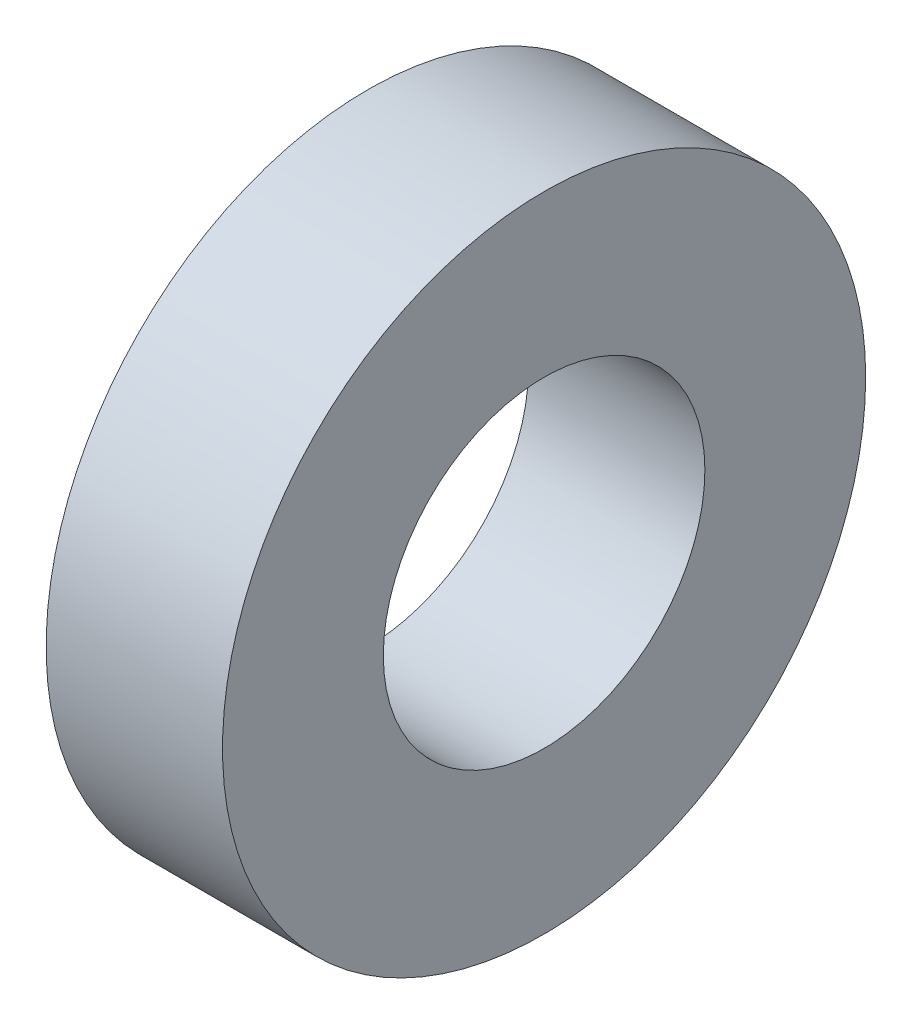
SolidWorks part; units mm, degrees
ref_plane "Front Plane" through (0, 0, 0) normal (0, 0, 1) x (1, 0, 0)
ref_plane "Top Plane" through (0, 0, 0) normal (0, 1, 0) x (1, 0, 0)
ref_plane "Right Plane" through (0, 0, 0) normal (1, 0, 0) x (0, 0, -1)
sketch "Sketch1" plane through (0, 0, 0) normal (1, 0, 0) x (0, 0, -1)
  circle A0 centre (0, 0) radius 6.35
  circle A1 centre (0, 0) radius 12.7
  dimension "D1" = 25.4
  dimension "D2" = 12.7
extrude "Boss-Extrude1" add sketch "Sketch1" along normal blind 6.9659
